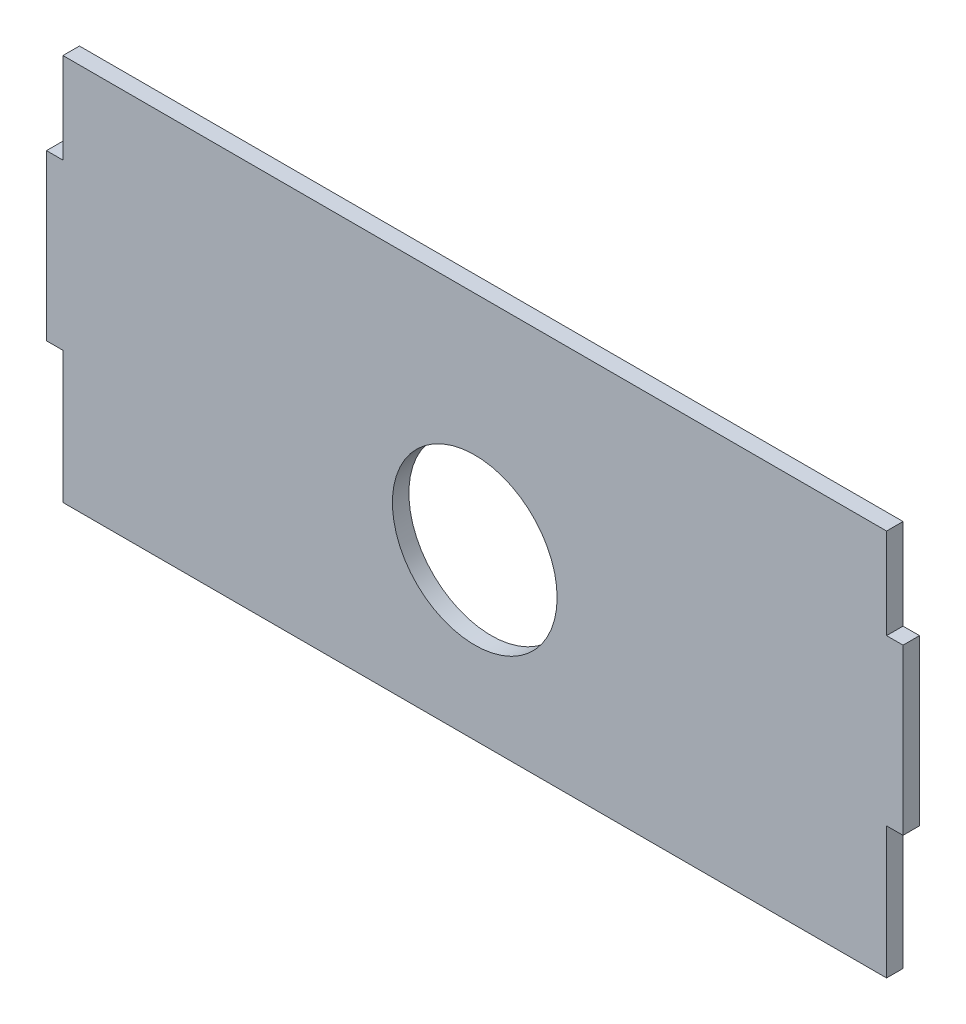
SolidWorks part; units mm, degrees
ref_plane "Спереди" through (0, 0, 0) normal (0, 0, 1) x (1, 0, 0)
ref_plane "Сверху" through (0, 0, 0) normal (0, 1, 0) x (1, 0, 0)
ref_plane "Справа" through (0, 0, 0) normal (1, 0, 0) x (0, 0, -1)
sketch "Эскиз1" plane through (0, 0, 0) normal (0, 0, 1) x (1, 0, 0)
  line L1 (0, 0) -> (100, 0)
  line L2 (0, 0) -> (0, 47)
  line L3 (0, 47) -> (100, 47)
  line L4 (100, 0) -> (100, 47)
  line L5 (100, 36) -> (102, 36)
  line L6 (100, 36) -> (100, 16)
  line L7 (100, 16) -> (102, 16)
  line L8 (102, 36) -> (102, 16)
  line L9 (0, 36) -> (-2, 36)
  line L10 (0, 36) -> (0, 16)
  line L11 (0, 16) -> (-2, 16)
  line L12 (-2, 36) -> (-2, 16)
  circle A0 centre (50, 20) radius 10
  point P13 (49.8362, 24.1809)
  point P14 (50, 47)
  point P15 (0, 23.5)
  dimension "D9" = 20
  dimension "D1" = 100
  dimension "D2" = 47
  dimension "D3" = 11
  dimension "D4" = 11
  dimension "D5" = 20
  dimension "D6" = 20
  dimension "D7" = 2
  dimension "D8" = 2
  dimension "D10" = 20
extrude "Бобышка-Вытянуть1" add sketch "Эскиз1" along normal blind 2 contours L8 L5 L4 L7 | L1 L4 L3 L2 | L12 L11 L10 L9
